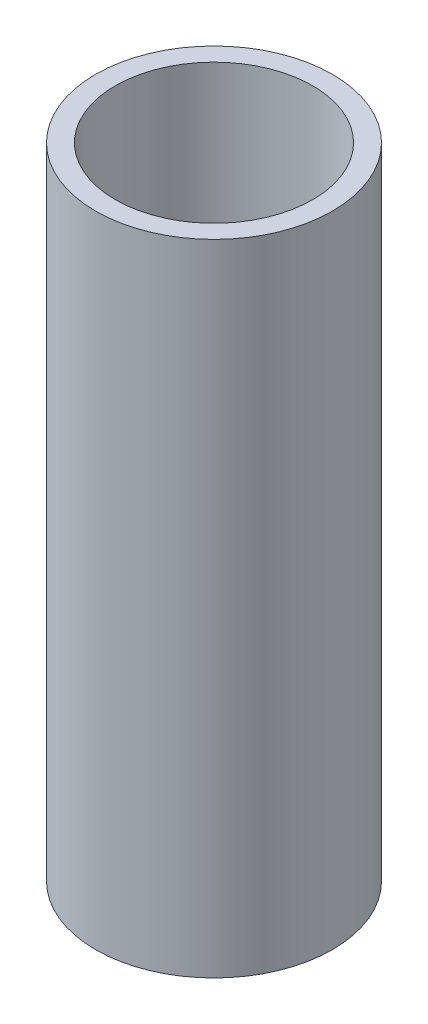
SolidWorks part; units mm, degrees
ref_plane "Front Plane" through (0, 0, 0) normal (0, 0, 1) x (1, 0, 0)
ref_plane "Top Plane" through (0, 0, 0) normal (0, 1, 0) x (1, 0, 0)
ref_plane "Right Plane" through (0, 0, 0) normal (1, 0, 0) x (0, 0, -1)
sketch "Sketch1" plane through (0, 0, 0) normal (0, 1, 0) x (1, 0, 0)
  circle A0 centre (0, 0) radius 30
  circle A1 centre (0, 0) radius 25
  dimension "D1" = 60
  dimension "D2" = 50
extrude "Boss-Extrude1" add sketch "Sketch1" along normal blind 162
